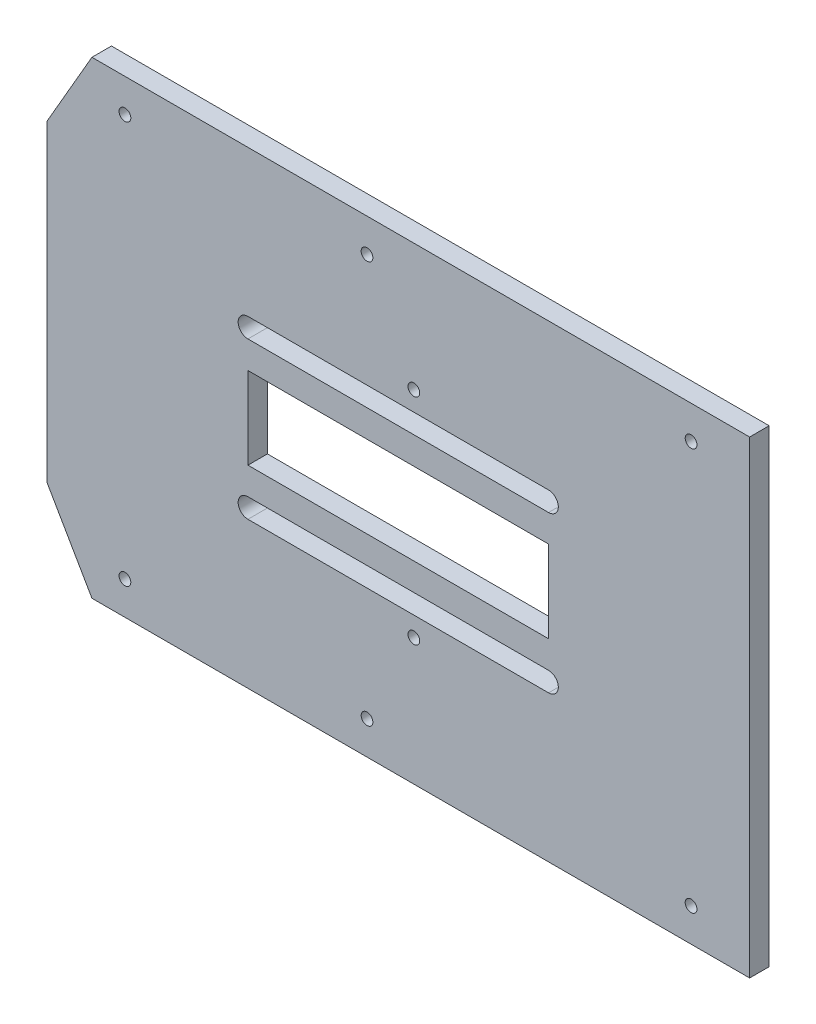
SolidWorks part; units mm, degrees
ref_plane "Plan de face" through (0, 0, 0) normal (0, 0, 1) x (1, 0, 0)
ref_plane "Plan de dessus" through (0, 0, 0) normal (0, 1, 0) x (1, 0, 0)
ref_plane "Plan de droite" through (0, 0, 0) normal (1, 0, 0) x (0, 0, -1)
sketch "Esquisse1" plane through (0, 0, 0) normal (0, 0, 1) x (1, 0, 0)
  line L0 (-90, 0) -> (90, 0)
  line L1 (90, 0) -> (90, 60)
  line L2 (90, 60) -> (-78.453, 60)
  line L3 (-78.453, 60) -> (-90, 40)
  line L4 (-90, 40) -> (-90, 0)
  point P2 (0, 0)
  dimension "D1" = 180
  dimension "D2" = 60
  dimension "D3" = 40
  dimension "D4" = 120
extrude "Boss.-Extru.1" add sketch "Esquisse1" along normal blind 5
mirror "Symétrie1" of "Boss.-Extru.1"
sketch "Esquisse2" plane through (0, 0, 5) normal (0, 0, 1) x (1, 0, 0)
  line L1 (-38.5, -10.5) -> (38.5, -10.5)
  line L2 (-38.5, -10.5) -> (-38.5, 10.5)
  line L3 (-38.5, 10.5) -> (38.5, 10.5)
  line L4 (38.5, -10.5) -> (38.5, 10.5)
  line L5 (-38.5, -10.5) -> (38.5, 10.5) construction
  line L6 (-38.5, 10.5) -> (38.5, -10.5) construction
  point P0 (0, 0)
  dimension "D1" = 77
  dimension "D2" = 21
extrude "Enlèv. mat.-Extru.1" cut sketch "Esquisse2" against normal up to next
sketch "Esquisse3" plane through (0, 0, 5) normal (0, 0, 1) x (1, 0, 0)
  line L0 (-38.5, 20) -> (38.5, 20) construction
  line L1 (-38.5, 22.5) -> (38.5, 22.5)
  line L2 (-38.5, 17.5) -> (38.5, 17.5)
  line L3 (38.5, 10.5) -> (-38.5, 10.5) construction
  line L4 (90, 60) -> (-78.453, 60) construction
  arc A0 (-38.5, 22.5) -> (-38.5, 17.5) centre (-38.5, 20) ccw
  arc A1 (38.5, 17.5) -> (38.5, 22.5) centre (38.5, 20) ccw
  point P2 (0, 20)
  dimension "D1" = 5
  dimension "D2" = 40
extrude "Enlèv. mat.-Extru.2" cut sketch "Esquisse3" against normal up to next
sketch "Esquisse4" plane through (0, 0, 0) normal (0, 0, -1) x (-1, 0, 0)
  circle A0 centre (-75, 51.5) radius 1.5
  circle A1 centre (8, 51.5) radius 1.5
  circle A2 centre (70, 51.5) radius 1.5
  circle A3 centre (-4, 27.5) radius 1.5
  dimension "D1" = 3
extrude "Enlèv. mat.-Extru.3" cut sketch "Esquisse4" against normal up to surface (5 mm away) up to face at (0, 20, 5)
mirror "Symétrie2" about plane through (0, 0, 0) normal (0, 1, 0) of "Enlèv. mat.-Extru.3"
mirror "Symétrie3" about plane through (0, 0, 0) normal (0, 1, 0) of "Enlèv. mat.-Extru.2"
